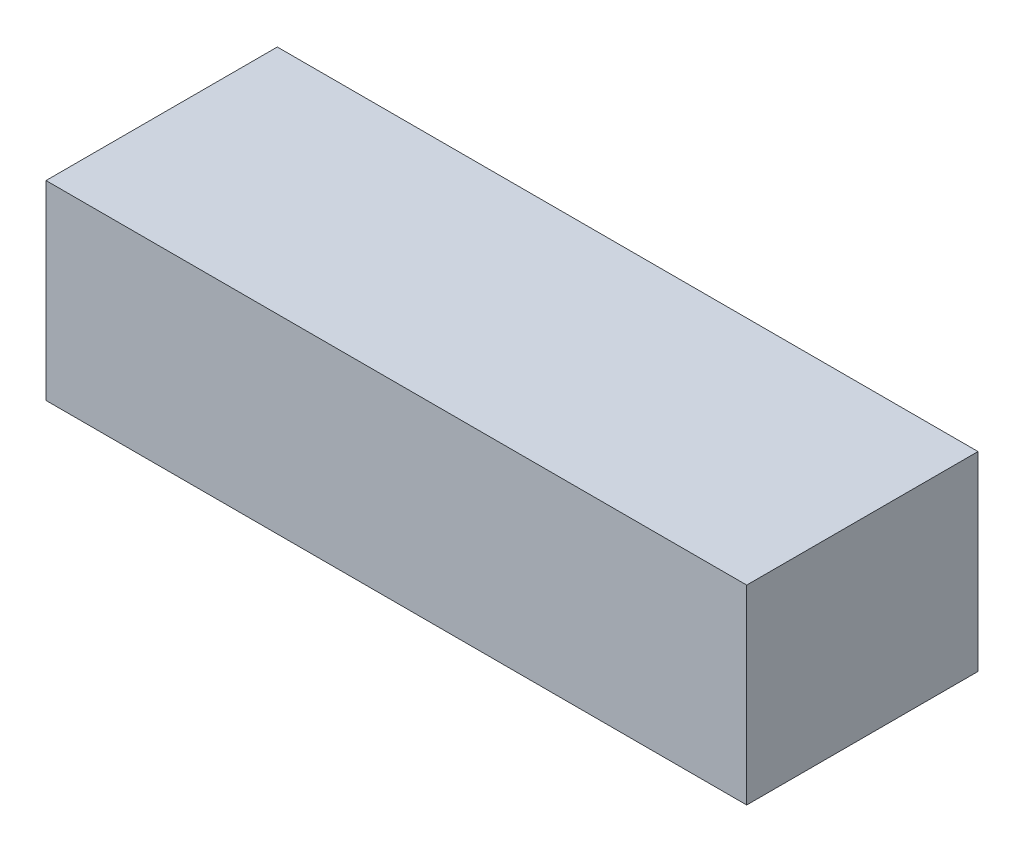
SolidWorks part; units mm, degrees
ref_plane "Front Plane" through (0, 0, 0) normal (0, 0, 1) x (1, 0, 0)
ref_plane "Top Plane" through (0, 0, 0) normal (0, 1, 0) x (1, 0, 0)
ref_plane "Right Plane" through (0, 0, 0) normal (1, 0, 0) x (0, 0, -1)
sketch "Sketch1" plane through (0, 0, 0) normal (0, 1, 0) x (1, 0, 0)
  line L1 (-51.5, -17) -> (51.5, -17)
  line L2 (-51.5, -17) -> (-51.5, 17)
  line L3 (-51.5, 17) -> (51.5, 17)
  line L4 (51.5, -17) -> (51.5, 17)
  line L5 (-51.5, -17) -> (51.5, 17) construction
  line L6 (-51.5, 17) -> (51.5, -17) construction
  point P0 (0, 0)
  dimension "D1" = 34
  dimension "D2" = 103
extrude "Boss-Extrude1" add sketch "Sketch1" along normal blind 28
